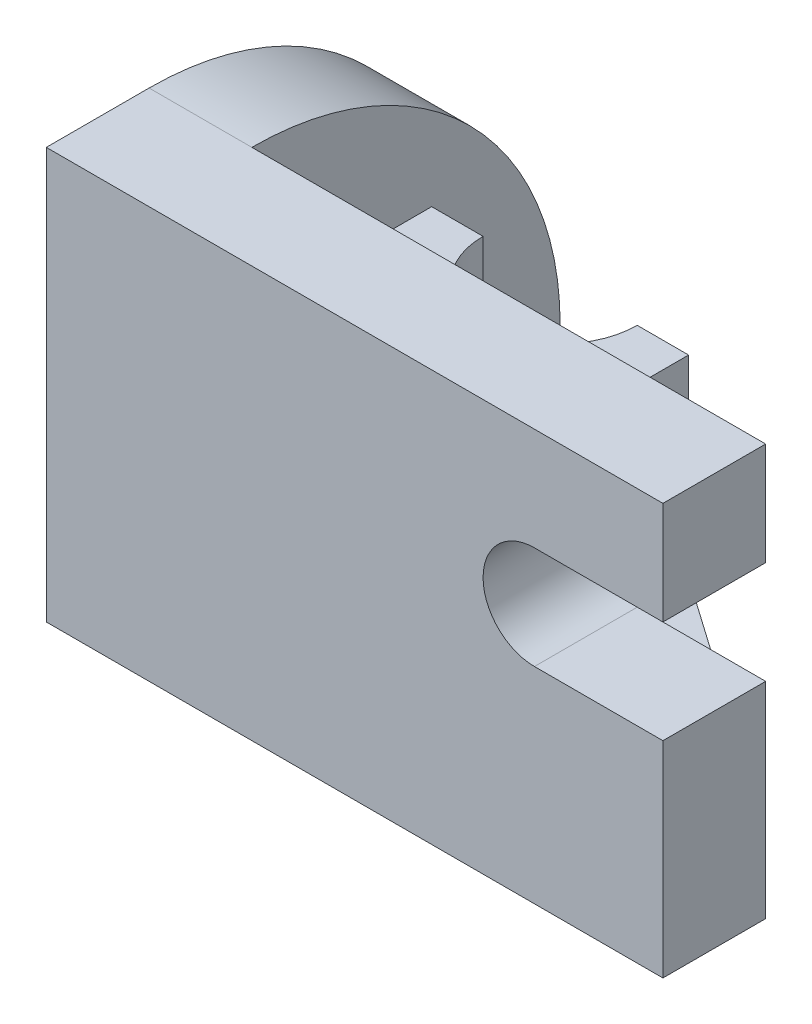
SolidWorks part; units mm, degrees
ref_plane "Front Plane" through (0, 0, 0) normal (0, 0, 1) x (1, 0, 0)
ref_plane "Top Plane" through (0, 0, 0) normal (0, 1, 0) x (1, 0, 0)
ref_plane "Right Plane" through (0, 0, 0) normal (1, 0, 0) x (0, 0, -1)
sketch "Sketch1" plane through (0, 0, 0) normal (0, 0, 1) x (1, 0, 0)
  line L1 (-48, 32) -> (48, 32)
  line L2 (-48, 32) -> (-48, -32)
  line L3 (-48, -32) -> (48, -32)
  line L4 (48, 32) -> (48, -32)
  line L5 (-48, 32) -> (48, -32) construction
  line L6 (-48, -32) -> (48, 32) construction
  point P0 (0, 0)
  dimension "D1" = 96
  dimension "D2" = 64
extrude "Boss-Extrude1" add sketch "Sketch1" along normal mid plane 16
sketch "Sketch2" plane through (0, 0, 8) normal (0, 0, 1) x (1, 0, 0)
  line L0 (48, -32) -> (48, 32) construction
  line L1 (48, 32) -> (-48, 32) construction
  line L2 (48, 0) -> (28, 0)
  line L3 (48, 0) -> (48, 16)
  line L4 (48, 16) -> (28, 16)
  line L5 (28, 0) -> (28, 16)
  circle A0 centre (28, 8) radius 8
  line M5 (48, -32) -> (48, 32)
  dimension "D1" = 16
  dimension "D2" = 16
  dimension "D3" = 20
extrude "Cut-Extrude1" cut sketch "Sketch2" against normal through all contours A0 L2 L4 M5 | L5 A0 | L5 A0
sketch "Sketch4" plane through (0, -32, 0) normal (0, -1, 0) x (1, 0, 0)
  line L0 (48, -8) -> (-48, -8) construction
  line L1 (-32, -8) -> (8, -8)
  line L2 (-32, -8) -> (-32, -36)
  line L3 (-32, -36) -> (8, -36)
  line L4 (8, -8) -> (8, -36)
  line L5 (-48, 8) -> (-48, -8) construction
  dimension "D1" = 40
  dimension "D2" = 28
  dimension "D3" = 16
extrude "Boss-Extrude2" add sketch "Sketch4" against normal blind 42
sketch "Sketch5" plane through (0, 10, 0) normal (0, 1, 0) x (1, 0, 0)
  line L0 (-32, 36) -> (8, 36) construction
  circle A0 centre (-12, 36) radius 12
extrude "Cut-Extrude2" cut sketch "Sketch5" against normal through all
sketch "Sketch6" plane through (0, -32, 0) normal (0, -1, 0) x (1, 0, 0)
  line L0 (8, -36) -> (48, -8)
  line L1 (48, -8) -> (8, -8)
  line L2 (8, -8) -> (8, -36)
extrude "Boss-Extrude3" add sketch "Sketch6" against normal blind 12
sketch "Sketch7" plane through (-48, 0, 0) normal (-1, 0, 0) x (0, 0, 1)
  line L0 (-8, -32) -> (-36, -32) construction
  line L1 (8, 32) -> (-8, 32)
  line L2 (8, 32) -> (8, -32)
  line L3 (8, -32) -> (-56, -32)
  line L4 (-56, -16) -> (-56, -32)
  arc A0 (-8, 32) -> (-56, -16) centre (-8, -16) ccw
  point P9 (-56, 32)
  dimension "D2" = 48
  dimension "D1" = 64
extrude "Boss-Extrude4" add sketch "Sketch7" against normal blind 16
